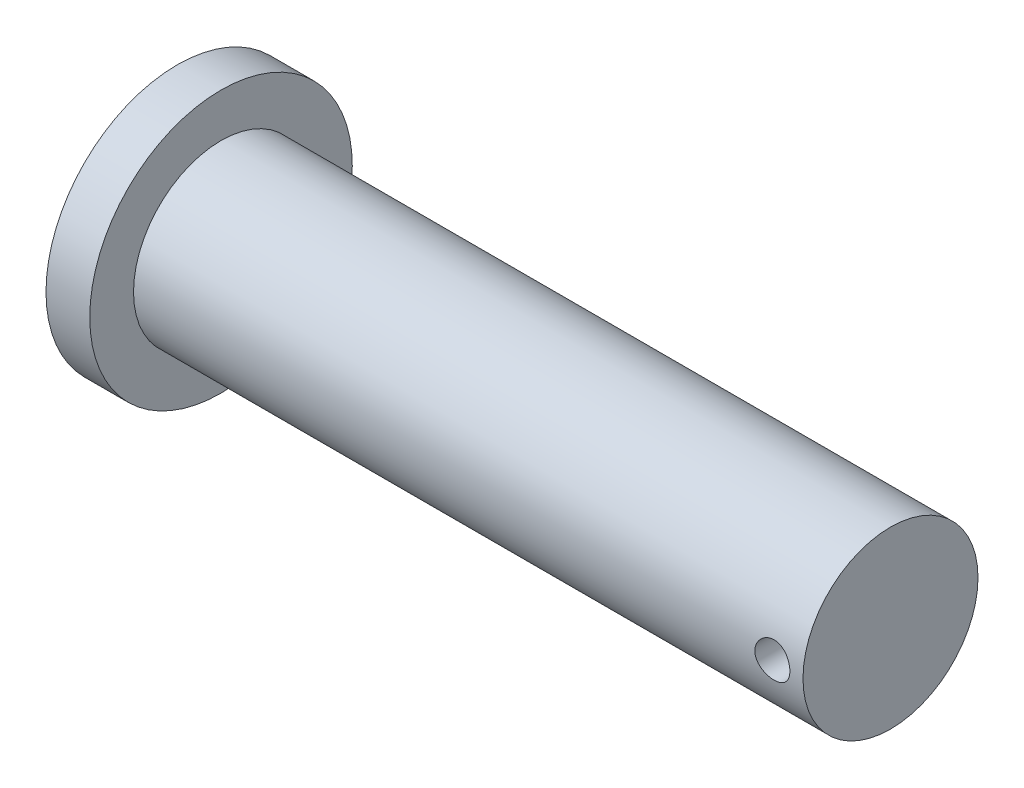
SolidWorks part; units mm, degrees
ref_plane "Front Plane" through (0, 0, 0) normal (0, 0, 1) x (1, 0, 0)
ref_plane "Top Plane" through (0, 0, 0) normal (0, 1, 0) x (1, 0, 0)
ref_plane "Right Plane" through (0, 0, 0) normal (1, 0, 0) x (0, 0, -1)
sketch "Sketch1" plane through (0, 0, 0) normal (1, 0, 0) x (0, 0, -1)
  circle A0 centre (0, 0) radius 10
extrude "Boss-Extrude1" add sketch "Sketch1" along normal blind 81.5
sketch "Sketch3" plane through (0, 0, 0) normal (0, 0, 1) x (1, 0, 0)
  line L0 (0, 0) -> (6, 0) construction
  line L1 (0, 10) -> (0, -10) construction
  line L2 (6, 0) -> (26, 0) construction
  line L3 (26, 0) -> (45.5, 0) construction
  line L4 (45.5, 0) -> (75.5, 0) construction
  line L5 (75.5, 0) -> (81.5, 0) construction
  line L6 (81.5, -10) -> (81.5, 10) construction
  circle A1 centre (78, 0) radius 2
  dimension "D5" = 2.5
  dimension "D6" = 4
  dimension "D1" = 6
  dimension "D2" = 6
  dimension "D3" = 20
  dimension "D4" = 30
extrude "Cut-Extrude1" cut sketch "Sketch3" against normal blind 19 and the other way blind 25
sketch "Sketch4" plane through (0, 0, 0) normal (-1, 0, 0) x (0, 0, 1)
  line L0 (0, -2) -> (0, 2) construction
  circle A0 centre (0, 0) radius 15
extrude "Boss-Extrude2" add sketch "Sketch4" against normal blind 5
scale "Scale1" scale about origin uniform scaling yes scale factor 0.5
